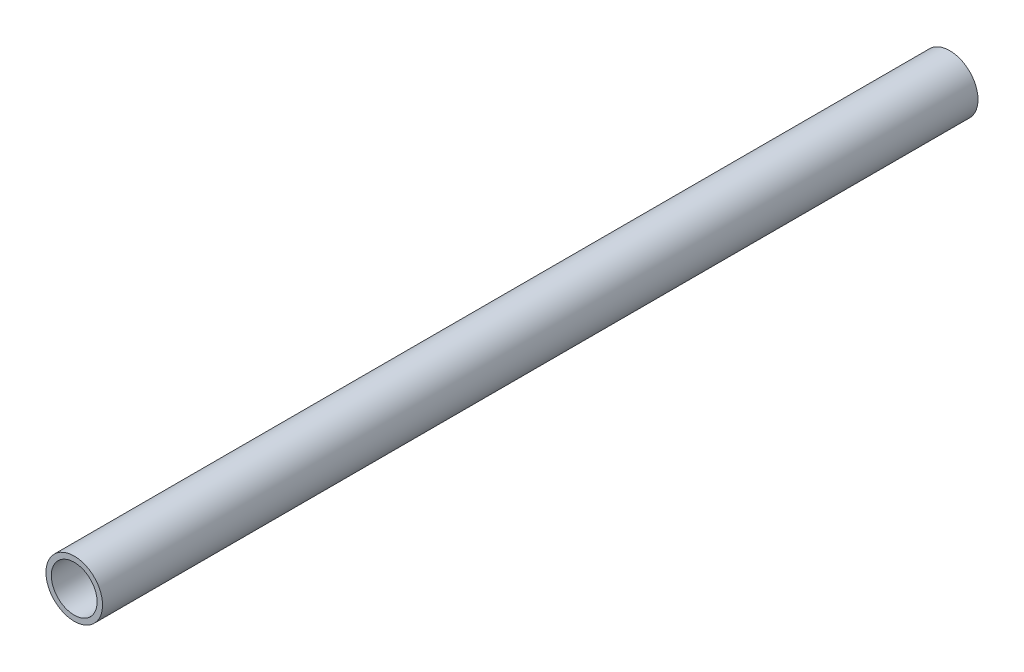
SolidWorks part; units mm, degrees
material "AISI 4130 Steel, annealed at 865C"
ref_plane "Front Plane" through (0, 0, 0) normal (0, 0, 1) x (1, 0, 0)
ref_plane "Top Plane" through (0, 0, 0) normal (0, 1, 0) x (1, 0, 0)
ref_plane "Right Plane" through (0, 0, 0) normal (1, 0, 0) x (0, 0, -1)
sketch "Sketch1" plane through (0, 0, 0) normal (0, 0, 1) x (1, 0, 0)
  circle A0 centre (0, 0) radius 6.477
  circle A1 centre (0, 0) radius 8.001
  dimension "D1" = 12.954
  dimension "D2" = 16.002
extrude "Boss-Extrude1" add sketch "Sketch1" along normal blind 247.65
sketch "Sketch2" plane through (0, 0, 0) normal (1, 0, 0) x (0, 0, -1)
  line L0 (0, 3.175) -> (-31.75, 3.175)
  line L1 (0, 55) -> (0, -55) construction
  line L2 (-31.75, -3.175) -> (0, -3.175)
  line L3 (-33.274, 1.651) -> (-33.274, -1.651)
  line L4 (0, -8.001) -> (0, 8.001) construction
  arc A0 (-33.274, 1.651) -> (-31.75, 3.175) centre (-31.75, 1.651) cw
  arc A1 (-31.75, -3.175) -> (-33.274, -1.651) centre (-31.75, -1.651) cw
  dimension "D5" = 31.75
  dimension "D6" = 33.274
  dimension "D1" = 33.274
  dimension "D2" = 31.75
  dimension "D3" = 6.35
  dimension "D4" = 3.175
